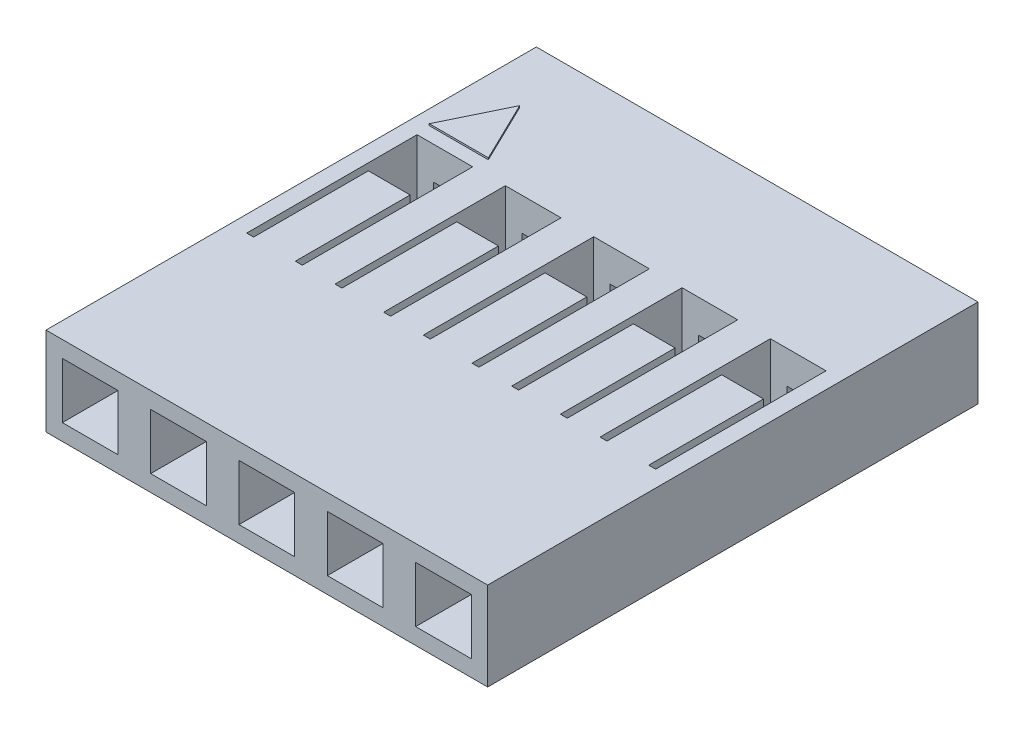
SolidWorks part; units mm, degrees
ref_plane "Front Plane" through (0, 0, 0) normal (0, 0, 1) x (1, 0, 0)
ref_plane "Top Plane" through (0, 0, 0) normal (0, 1, 0) x (1, 0, 0)
ref_plane "Right Plane" through (0, 0, 0) normal (1, 0, 0) x (0, 0, -1)
sketch "Sketch1" plane through (0, 0, 0) normal (0, 0, 1) x (1, 0, 0)
  line L0 (0, 0) -> (0, 2.54)
  line L1 (0, 2.54) -> (2.54, 2.54)
  line L2 (2.54, 2.54) -> (2.54, 0)
  line L3 (2.54, 0) -> (0, 0)
  line L4 (1.27, 2.54) -> (1.27, 0) construction
  line L5 (0, 1.27) -> (2.54, 1.27) construction
  line L7 (0.945, 0.945) -> (1.595, 0.945)
  line L8 (0.945, 0.945) -> (0.945, 1.595)
  line L9 (0.945, 1.595) -> (1.595, 1.595)
  line L10 (1.595, 0.945) -> (1.595, 1.595)
  line L11 (0.945, 0.945) -> (1.595, 1.595) construction
  line L12 (0.945, 1.595) -> (1.595, 0.945) construction
  point P9 (1.27, 1.27)
  dimension "D1" = 2.54
  dimension "D2" = 0.65
extrude "Boss-Extrude1" add sketch "Sketch1" along normal blind 14.1
chamfer "Chamfer1" distance 0.5 angle 45 4 edges at (1.27, 0.945, 0) (0.945, 1.27, 0) (1.595, 1.27, 0) (1.27, 1.595, 0)
sketch "Sketch4" plane through (0, 2.54, 0) normal (0, 1, 0) x (1, 0, 0)
  line L0 (1.27, 0) -> (1.27, -14.1) construction
  line L1 (2.54, 0) -> (0, 0) construction
  line L2 (2.54, -14.1) -> (0, -14.1) construction
  line L4 (2.07, -5.5) -> (0.47, -5.5)
  line L5 (2.07, -5.5) -> (2.07, -3.9)
  line L6 (2.07, -3.9) -> (0.47, -3.9)
  line L7 (0.47, -5.5) -> (0.47, -3.9)
  line L8 (2.07, -5.5) -> (0.47, -3.9) construction
  line L9 (2.07, -3.9) -> (0.47, -5.5) construction
  point P6 (1.27, -4.7)
  dimension "D1" = 1.6
  dimension "D2" = 3.9
extrude "Cut-Extrude2" cut sketch "Sketch4" against normal blind 1.5
sketch "Sketch2" plane through (0, 0, 14.1) normal (0, 0, 1) x (1, 0, 0)
  line L8 (0.47, 0.47) -> (2.07, 0.47)
  line L9 (2.07, 0.47) -> (2.07, 2.07)
  line L10 (0.47, 2.07) -> (0.47, 0.47)
  line L11 (2.07, 2.07) -> (0.47, 2.07)
  line L12 (0.47, 0.47) -> (2.07, 0.47)
  line L13 (2.07, 0.47) -> (2.07, 2.07)
  line L14 (0.47, 2.07) -> (0.47, 0.47)
  line L15 (2.07, 2.07) -> (0.47, 2.07)
  dimension "D1" = 0.475
extrude "Cut-Extrude1" cut sketch "Sketch2" against normal up to surface (10.2 mm away)
sketch "Sketch3" plane through (0, 2.54, 0) normal (0, 1, 0) x (1, 0, 0)
  line L0 (0, -3.5) -> (2.54, -3.5) construction
  line L1 (0, -14.1) -> (0, 0) construction
  line L2 (2.54, -14.1) -> (2.54, 0) construction
  line L3 (2.54, 0) -> (0, 0) construction
  line L4 (1.27, -3.5) -> (1.27, 0) construction
  line L5 (2.12, -3.5) -> (0.42, -3.5)
  line L6 (0.42, -3.5) -> (1.27, -1.75)
  line L7 (2.12, -3.5) -> (1.27, -1.75)
  dimension "D1" = 3.5
  dimension "D2" = 1.7
extrude "Boss-Extrude2" add sketch "Sketch3" along normal blind 0.05
sketch "Sketch5" plane through (0, 2.54, 0) normal (0, 1, 0) x (1, 0, 0)
  line L0 (1.27, 0) -> (1.27, -14.1) construction
  line L1 (2.54, 0) -> (0, 0) construction
  line L2 (2.54, -14.1) -> (0, -14.1) construction
  line L3 (0.47, -5.5) -> (0.47, -8.8)
  line L4 (0.47, -5.5) -> (2.07, -5.5) construction
  line L5 (0.47, -8.8) -> (0.67, -8.8)
  line L6 (0.67, -8.8) -> (0.67, -5.5)
  line L7 (0.67, -5.5) -> (0.47, -5.5)
  line L8 (0.47, -3.9) -> (0.47, -14.1) construction
  line L9 (1.87, -8.8) -> (1.87, -5.5)
  line L10 (2.07, -8.8) -> (1.87, -8.8)
  line L11 (2.07, -5.5) -> (2.07, -8.8)
  line L12 (1.87, -5.5) -> (2.07, -5.5)
  dimension "D1" = 0.6
  dimension "D2" = 3.3
extrude "Cut-Extrude3" cut sketch "Sketch5" against normal up to surface (0.47 mm away) up to face at (1.27, 2.07, 9.8)
pattern_linear "LPattern1" count 5 spacing 2.54 along (1, 0, 0) of "Boss-Extrude1", "Cut-Extrude1", "Cut-Extrude2", "Cut-Extrude3", "Chamfer1"
